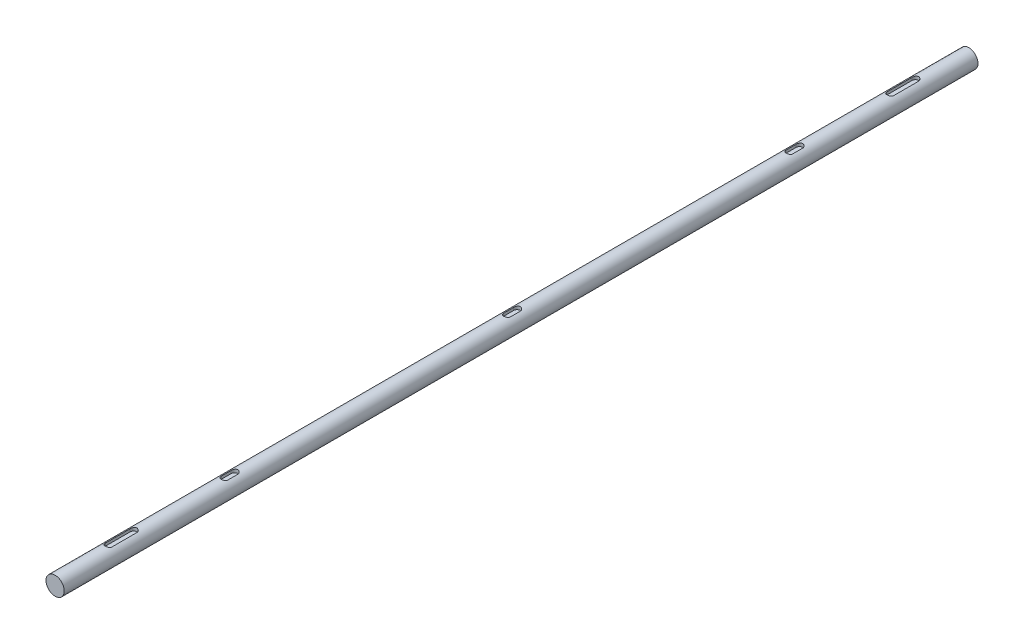
SolidWorks part; units mm, degrees
ref_plane "前视基准面" through (0, 0, 0) normal (0, 0, 1) x (1, 0, 0)
ref_plane "上视基准面" through (0, 0, 0) normal (0, 1, 0) x (1, 0, 0)
ref_plane "右视基准面" through (0, 0, 0) normal (1, 0, 0) x (0, 0, -1)
sketch "草图1" plane through (0, 0, 0) normal (0, 0, 1) x (1, 0, 0)
  circle A0 centre (0, 0) radius 5.5
  dimension "D1" = 11
extrude "凸台-拉伸1" add sketch "草图1" along normal mid plane 550
ref_plane "基准面1" through (0, 5.5, 0) normal (0, 1, 0) x (1, 0, 0)
sketch "草图2" plane through (0, 5.5, 0) normal (0, 1, 0) x (1, 0, 0)
  line L0 (0, 3) -> (0, -3) construction
  line L1 (2, 3) -> (2, -3)
  line L2 (-2, 3) -> (-2, -3)
  arc A0 (2, 3) -> (-2, 3) centre (0, 3) ccw
  arc A1 (-2, -3) -> (2, -3) centre (0, -3) ccw
  point P3 (0, 0)
  dimension "D1" = 2
  dimension "D2" = 6
extrude "切除-拉伸1" cut sketch "草图2" against normal blind 2
sketch "草图3" plane through (0, 5.5, 0) normal (0, 1, 0) x (1, 0, 0)
  line L0 (0, 173) -> (0, 167) construction
  line L1 (2, 173) -> (2, 167)
  line L2 (-2, 173) -> (-2, 167)
  line L3 (0, 0) -> (-19.0389, 0) construction
  line L4 (0, -173) -> (0, -167) construction
  line L5 (2, -173) -> (2, -167)
  line L6 (-2, -173) -> (-2, -167)
  arc A0 (2, 173) -> (-2, 173) centre (0, 173) ccw
  arc A1 (-2, 167) -> (2, 167) centre (0, 167) ccw
  arc A2 (2, -173) -> (-2, -173) centre (0, -173) cw
  arc A3 (-2, -167) -> (2, -167) centre (0, -167) cw
  point P3 (0, 170)
  point P12 (0, -170)
  dimension "D1" = 2
  dimension "D2" = 6
  dimension "D3" = 170
extrude "切除-拉伸2" cut sketch "草图3" against normal blind 2
sketch "草图4" plane through (0, 5.5, 0) normal (0, 1, 0) x (1, 0, 0)
  line L0 (0, -242.778) -> (0, -227.778) construction
  line L1 (-2, -242.778) -> (-2, -227.778)
  line L2 (2, -242.778) -> (2, -227.778)
  line L3 (0, 0) -> (52.9793, 0) construction
  line L4 (0, 242.778) -> (0, 227.778) construction
  line L5 (-2, 242.778) -> (-2, 227.778)
  line L6 (2, 242.778) -> (2, 227.778)
  arc A0 (-2, -242.778) -> (2, -242.778) centre (0, -242.778) ccw
  arc A1 (2, -227.778) -> (-2, -227.778) centre (0, -227.778) ccw
  arc A2 (-2, 242.778) -> (2, 242.778) centre (0, 242.778) cw
  arc A3 (2, 227.778) -> (-2, 227.778) centre (0, 227.778) cw
  point P3 (0, -235.278)
  point P12 (0, 235.278)
  dimension "D1" = 2
  dimension "D2" = 15
extrude "切除-拉伸3" cut sketch "草图4" against normal blind 2
